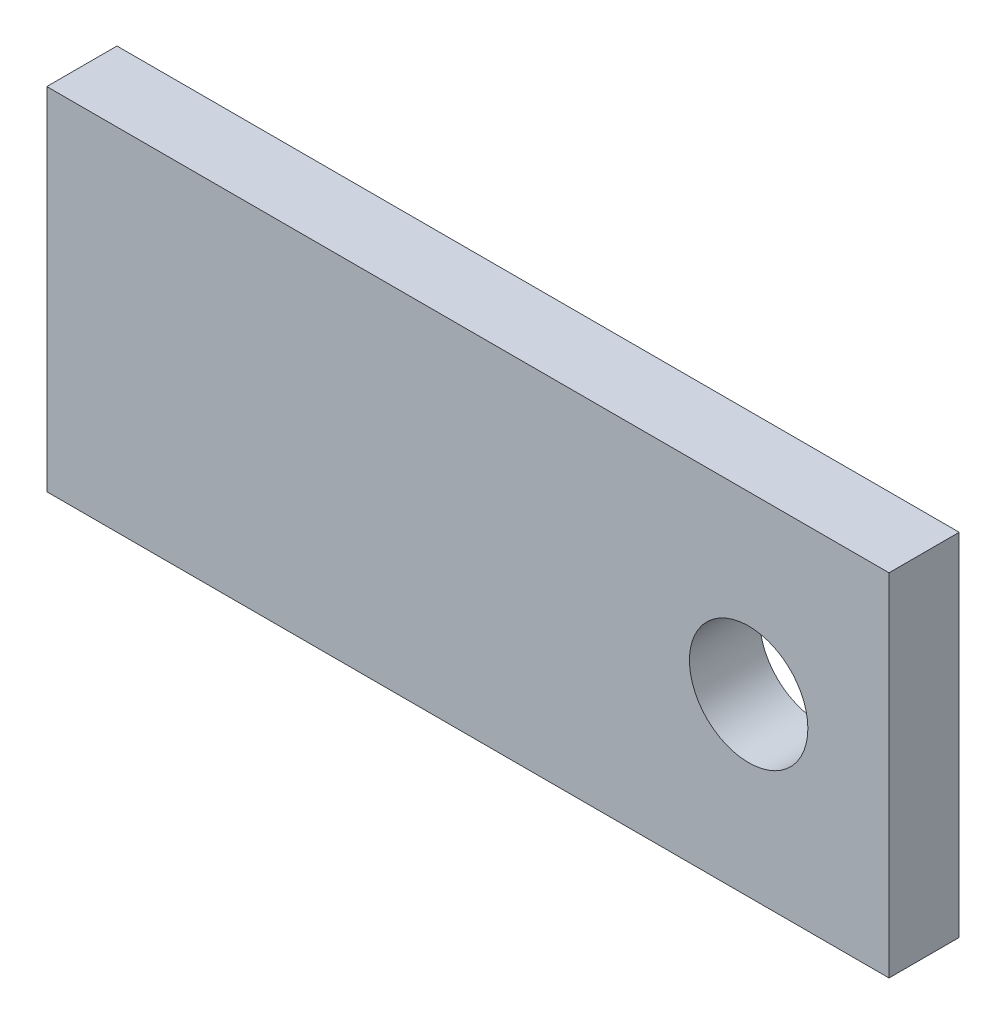
SolidWorks part; units mm, degrees
material "Plain Carbon Steel"
ref_plane "Front Plane" through (0, 0, 0) normal (0, 0, 1) x (1, 0, 0)
ref_plane "Top Plane" through (0, 0, 0) normal (0, 1, 0) x (1, 0, 0)
ref_plane "Right Plane" through (0, 0, 0) normal (1, 0, 0) x (0, 0, -1)
sketch "Sketch1" plane through (0, 0, 0) normal (0, 0, 1) x (1, 0, 0)
  line L1 (-38.1, -15.875) -> (38.1, -15.875)
  line L2 (-38.1, -15.875) -> (-38.1, 15.875)
  line L3 (-38.1, 15.875) -> (38.1, 15.875)
  line L4 (38.1, -15.875) -> (38.1, 15.875)
  line L5 (-38.1, -15.875) -> (38.1, 15.875) construction
  line L6 (-38.1, 15.875) -> (38.1, -15.875) construction
  point P0 (0, 0)
  dimension "D1" = 76.2
  dimension "D2" = 31.75
extrude "Extrude1" add sketch "Sketch1" along normal mid plane 6.35
sketch "Sketch2" plane through (0, 0, 3.175) normal (0, 0, 1) x (1, 0, 0)
  line L0 (38.1, 0) -> (25.4, 0) construction
  line L1 (38.1, -15.875) -> (38.1, 15.875) construction
  dimension "D1" = 12.7
hole_wizard "27/64 (0.42188) Diameter Hole1" positions "3DSketch1" profile "Sketch4" hole size "27/64" standard "Ansi Inch" end condition through all
sketch3d "3DSketch1"
  point P0 (25.4, 0, 3.175)
sketch "Sketch4" plane through (25.4, 0, 3.175) normal (1, 0, 0) x (0, -1, 0)
  line L0 (0, 0) -> (0, 6.35)
  line L1 (0, 6.35) -> (5.3579, 6.35)
  line L2 (5.3579, 6.35) -> (5.3579, 0)
  line L5 (5.3579, 0) -> (0, 0)
  line L11 (0, -6.35) -> (0, 107.95) construction
  dimension "Thru Hole Dia." = 10.7158
  dimension "Thru Hole Depth" = 6.35
sketch "Sketch5" plane through (0, 0, 0) normal (0, 0, 1) x (1, 0, 0)
  point P0 (25.4, 0)
